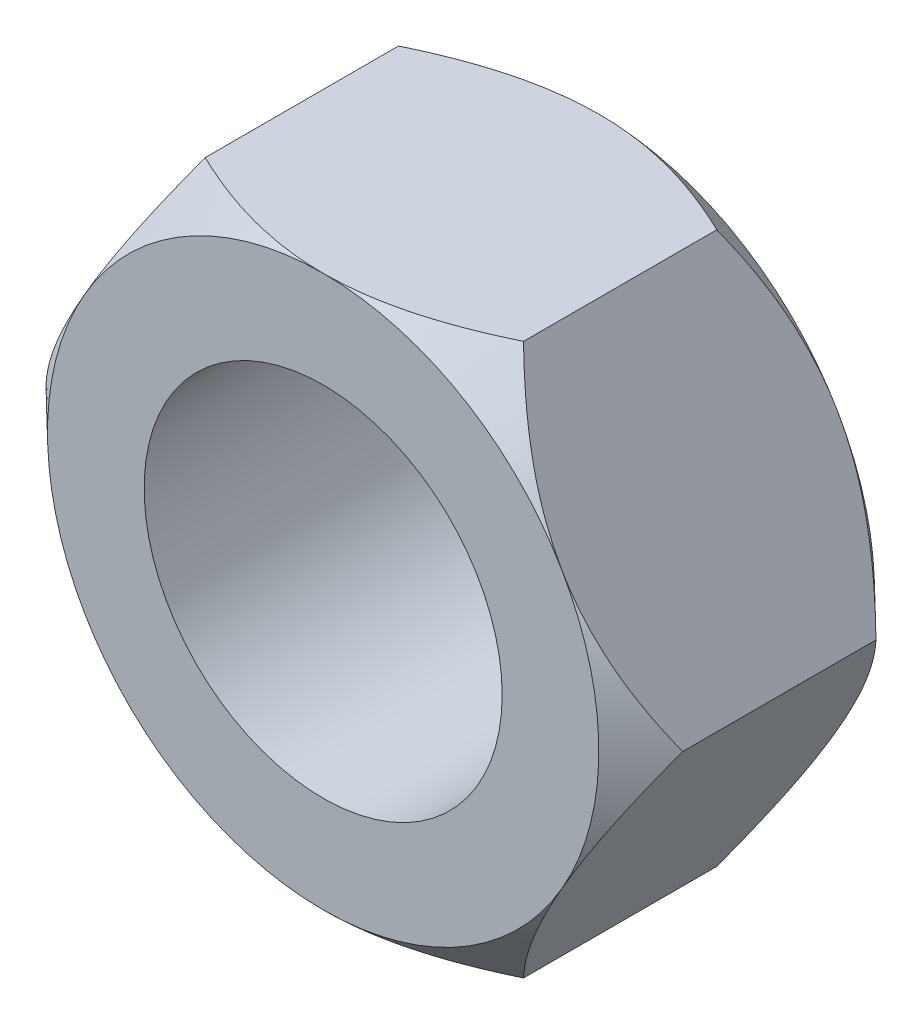
SolidWorks part; units mm, degrees
ref_plane "Alzado" through (0, 0, 0) normal (0, 0, 1) x (1, 0, 0)
ref_plane "Planta" through (0, 0, 0) normal (0, 1, 0) x (1, 0, 0)
ref_plane "Vista lateral" through (0, 0, 0) normal (1, 0, 0) x (0, 0, -1)
sketch "Croquis1" plane through (0, 0, 0) normal (0, 0, 1) x (1, 0, 0)
  line L1 (12.7017, 0) -> (6.3509, 11)
  line L2 (6.3509, 11) -> (-6.3509, 11)
  line L3 (-6.3509, 11) -> (-12.7017, 0)
  line L4 (-12.7017, 0) -> (-6.3509, -11)
  line L5 (-6.3509, -11) -> (6.3509, -11)
  line L6 (6.3509, -11) -> (12.7017, 0)
  circle A0 centre (0, 0) radius 7.1437
  circle A1 centre (0, 0) radius 11 construction
  dimension "D1" = 14.2875
  dimension "D2" = 22
extrude "Saliente-Extruir1" add sketch "Croquis1" along normal blind 11
sketch "Croquis2" plane through (0, 0, 11) normal (0, 0, 1) x (1, 0, 0)
  circle A0 centre (0, 0) radius 11
  circle A1 centre (0, 0) radius 31.2231
extrude "Cortar-Extruir1" cut sketch "Croquis2" against normal blind 10 draft 46
sketch "Croquis4" plane through (0, 0, 0) normal (0, 0, -1) x (-1, 0, 0)
  circle A0 centre (0, 0) radius 11
  circle A1 centre (0, 0) radius 40.8627
extrude "Cortar-Extruir3" cut sketch "Croquis4" against normal blind 10 draft 46
